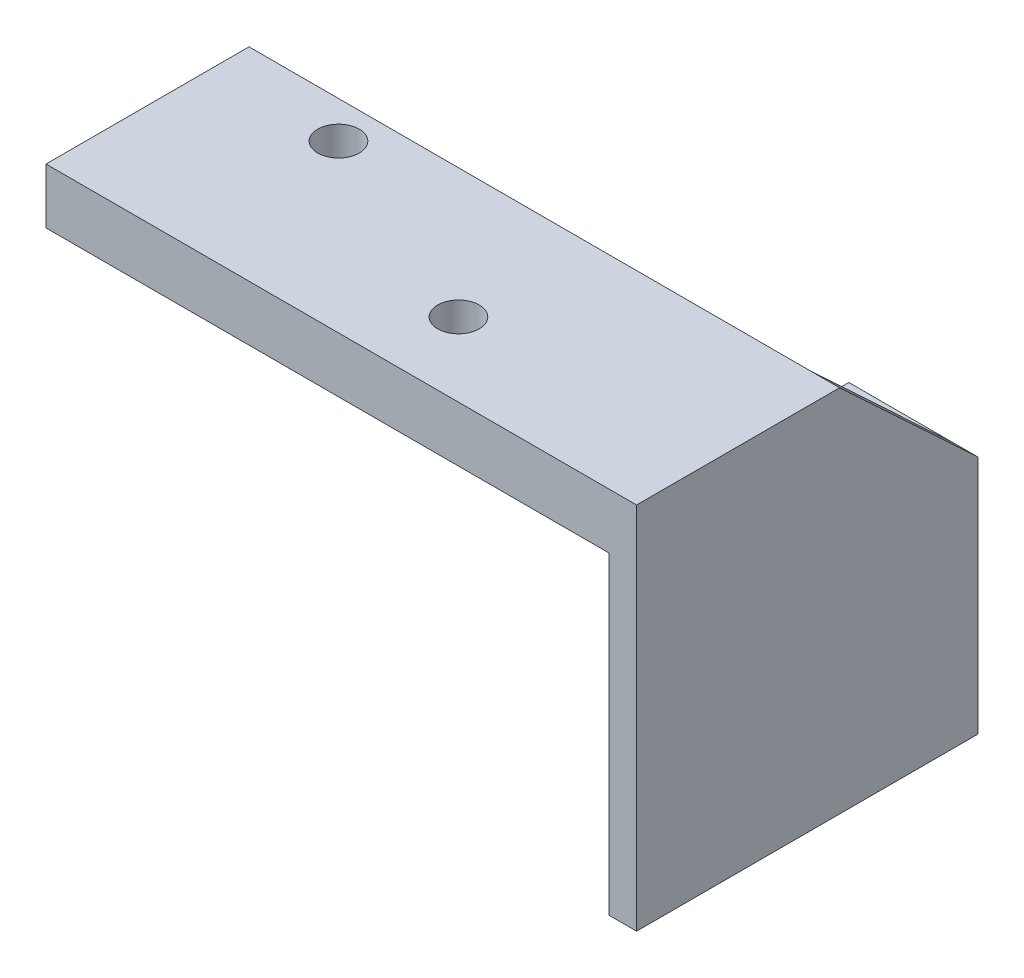
SolidWorks part; units mm, degrees
ref_plane "Plan de face" through (0, 0, 0) normal (0, 0, 1) x (1, 0, 0)
ref_plane "Plan de dessus" through (0, 0, 0) normal (0, 1, 0) x (1, 0, 0)
ref_plane "Plan de droite" through (0, 0, 0) normal (1, 0, 0) x (0, 0, -1)
sketch "Esquisse1" plane through (0, 0, 0) normal (0, 0, 1) x (1, 0, 0)
  line L1 (5.5, 13) -> (-5.5, 13)
  line L2 (5.5, 13) -> (5.5, -13)
  line L3 (5.5, -13) -> (-5.5, -13)
  line L4 (-5.5, 13) -> (-5.5, -13)
  line L5 (5.5, 13) -> (-5.5, -13) construction
  line L6 (5.5, -13) -> (-5.5, 13) construction
  point P4 (0, 0)
  dimension "D1" = 11
  dimension "D2" = 26
extrude "Boss.-Extru.1" add sketch "Esquisse1" along normal blind 9
hole_wizard "Chambrage pour vis à tête ronde bombée M31" positions "Esquisse5" profile "Esquisse7" counterbore size "M3" standard "Ansi Metric" end condition through all
sketch "Esquisse5" plane through (0, 0, 9) normal (0, 0, 1) x (1, 0, 0)
  line L0 (5.5, 13) -> (-5.5, 13) construction
  point P0 (0, 7.5)
  point P2 (0, -7.5)
  point P8 (0, 13)
  dimension "D1" = 15
  dimension "D2" = 5.5
sketch "Esquisse7" plane through (0, 7.5, 9) normal (1, 0, 0) x (0, -1, 0)
  line L0 (0, 0) -> (0, 9)
  line L1 (0, 9) -> (1.7, 9)
  line L3 (1.7, 9) -> (1.7, 2.4)
  line L4 (1.7, 2.4) -> (3.5, 2.4)
  line L5 (3.5, 2.4) -> (3.5, 0)
  line L7 (3.5, 0) -> (0, 0)
  line L11 (0, -6.35) -> (0, 107.95) construction
  dimension "Diamètre du perçage jusqu'au prochain" = 3.4
  dimension "Profondeur du perçage jusqu'au prochain" = 9
  dimension "Diamètre du chambrage" = 7
  dimension "Profondeur du chambrage" = 2.4
sketch "Esquisse8" plane through (0, -13, 0) normal (0, -1, 0) x (1, 0, 0)
  line L1 (-55.5, 0) -> (-55.5, 37)
  line L2 (-55.5, 37) -> (5.5, 37)
  line L3 (5.5, 9) -> (5.5, 37)
  line L5 (-5.5, 9) -> (-5.5, 0) construction
  line L7 (-5.5, 0) -> (-5.5, 9)
  line L8 (5.5, 9) -> (-5.5, 9) construction
  line L9 (-5.5, 9) -> (5.5, 9)
  line L10 (-5.5, 0) -> (-55.5, 0)
  dimension "D1" = 50
  dimension "D2" = 28
extrude "Boss.-Extru.2" add sketch "Esquisse8" against normal blind 40
hole_wizard "Diamètre du perçage Ø4.5 (4.5)1" positions "Esquisse12" profile "Esquisse14" hole size "Ø4.5" standard "Ansi Metric" end condition through all
sketch "Esquisse12" plane through (0, 27, 0) normal (0, 1, 0) x (1, 0, 0)
  line L1 (5.5, -9) -> (5.5, 0) construction
  point P0 (-41.8014, -19.0006)
  point P2 (-18.8014, -29.0006)
  dimension "D1" = 10
  dimension "D2" = 23
  dimension "D3" = 24.3014
  dimension "D4" = 29.0006
sketch "Esquisse14" plane through (-41.8014, 27, 19.0006) normal (1, 0, 0) x (0, 0, 1)
  line L0 (0, 0) -> (0, 40)
  line L1 (0, 40) -> (2.25, 40)
  line L2 (2.25, 40) -> (2.25, 0)
  line L5 (2.25, 0) -> (0, 0)
  line L11 (0, -6.35) -> (0, 107.95) construction
  dimension "Diamètre du perçage jusqu'au prochain" = 4.5
  dimension "Profondeur du perçage jusqu'au prochain" = 40
sketch "Esquisse20" plane through (0, 27, 0) normal (0, 1, 0) x (1, 0, 0)
  line L1 (-5.5, -9) -> (5.5, -9)
  line L2 (-5.5, -9) -> (-5.5, -37)
  line L3 (-5.5, -37) -> (5.5, -37)
  line L4 (5.5, -9) -> (5.5, -37)
  line L5 (-5.5, -9) -> (5.5, -37) construction
  line L6 (-5.5, -37) -> (5.5, -9) construction
  point P4 (0, -23)
  point P7 (0, 0)
  point P8 (0, 0)
  dimension "D1" = 11
  dimension "D2" = 28
extrude "Enlèv. mat.-Extru.6" cut sketch "Esquisse20" against normal through all
sketch "Esquisse21" plane through (0, 0, 37) normal (0, 0, 1) x (1, 0, 0)
  line L0 (-55.5, 27) -> (-55.5, -13) construction
  line L1 (-55.5, -13) -> (-5.5, -13)
  line L2 (-55.5, -13) -> (-55.5, 21)
  line L3 (-55.5, 21) -> (-5.5, 21)
  line L4 (-5.5, -13) -> (-5.5, 21)
  line L5 (-55.5, -13) -> (-5.5, 21) construction
  line L6 (-55.5, 21) -> (-5.5, -13) construction
  line L7 (-5.5, -13) -> (-5.5, 13) construction
  line L8 (-5.5, 27) -> (-55.5, 27) construction
  point P4 (-30.5, 4)
  point P11 (-55.5, -13)
  point P12 (-5.5, -13.3179)
  point P13 (-5.5, -8.6753)
  dimension "D1" = 6
extrude "Enlèv. mat.-Extru.7" cut sketch "Esquisse21" against normal through all
sketch "Esquisse23" plane through (0, 0, 37) normal (0, 0, 1) x (1, 0, 0)
  line L0 (-5.5, 27) -> (-5.5, 13)
  line L1 (-5.5, -13) -> (-5.5, 13) construction
  line L2 (-5.5, 13) -> (5.5, 13)
  line L3 (5.5, 13) -> (-5.5, 13) construction
  line L4 (5.5, 13) -> (5.5, 27)
  line L5 (5.5, 27) -> (-5.5, 27)
  line L6 (-5.5, 21) -> (-5.5, 27) construction
  line L7 (-5.5, 27) -> (-55.5, 27) construction
  point P7 (1.6892, 25.9573)
  point P9 (0, 0)
  point P11 (-5.5, 27)
extrude "Boss.-Extru.3" add sketch "Esquisse23" against normal through all
sketch "Esquisse24" plane through (5.5, 0, 0) normal (1, 0, 0) x (0, 0, -1)
  line L0 (-37, 27) -> (-37, -13)
  line L2 (-37, 13) -> (-37, 27) construction
  line L3 (0, 27) -> (-37, 27) construction
  line L4 (-37, 27) -> (0, 27)
  line L5 (0, -13) -> (0, 27) construction
  line L6 (0, 27) -> (0, -13)
  line L7 (-9, -13) -> (0, -13) construction
  line L8 (0, -13) -> (-37, -13)
extrude "Boss.-Extru.4" add sketch "Esquisse24" along normal blind 3
sketch "Esquisse27" plane through (0, 21, 0) normal (0, -1, 0) x (1, 0, 0)
  line L0 (-55.5, 0) -> (8.5, 0) construction
  line L1 (5.5, 0) -> (-5.5, 0)
  line L2 (5.5, 0) -> (5.5, 37)
  line L3 (5.5, 37) -> (-5.5, 37)
  line L4 (-5.5, 0) -> (-5.5, 37)
  line L5 (5.5, 0) -> (-5.5, 37) construction
  line L6 (5.5, 37) -> (-5.5, 0) construction
  line L8 (5.5, 9) -> (5.5, 37) construction
  line L9 (-5.5, 37) -> (-55.5, 37) construction
  point P4 (0, 18.5)
  point P7 (-6.8727, 17.1669)
  point P8 (3.9486, 0)
  point P9 (5.5, 13)
  point P14 (-5.5, 37)
extrude "Enlèv. mat.-Extru.11" cut sketch "Esquisse27" along normal blind 8
sketch "Esquisse28" plane through (0, 27, 0) normal (0, 1, 0) x (1, 0, 0)
  line L1 (-55.5, 0) -> (8.5, 0)
  line L2 (-55.5, 0) -> (-55.5, -15)
  line L3 (-55.5, -15) -> (8.5, -15)
  line L4 (8.5, 0) -> (8.5, -15)
  line L5 (-55.5, 0) -> (8.5, -15) construction
  line L6 (-55.5, -15) -> (8.5, 0) construction
  line L7 (-55.5, 0) -> (8.5, 0) construction
  line L8 (8.5, 0) -> (8.5, -37) construction
  point P4 (-23.5, -7.5)
  point P6 (8.2874, 0)
  point P9 (0, 0)
  dimension "D1" = 15
extrude "Enlèv. mat.-Extru.12" cut sketch "Esquisse28" against normal up to surface (6 mm away) up to face at (-41.8014, 21, 21.2506)
sketch "Esquisse30" plane through (5.5, 0, 0) normal (-1, 0, 0) x (0, 0, 1)
  line L0 (15, 21) -> (15, 13)
  line L1 (0, 13) -> (15, 13)
  line L2 (0, 21) -> (15, 21)
  line L3 (0, 21) -> (0, 13)
extrude "Enlèv. mat.-Extru.13" cut sketch "Esquisse30" against normal through all
sketch "Esquisse31" plane through (5.5, 0, 0) normal (-1, 0, 0) x (0, 0, 1)
  line L0 (15, 27) -> (0, 13)
  line L1 (0, 13) -> (15, 13)
  line L2 (15, 13) -> (15, 27)
extrude "Boss.-Extru.6" add sketch "Esquisse31" against normal through all
